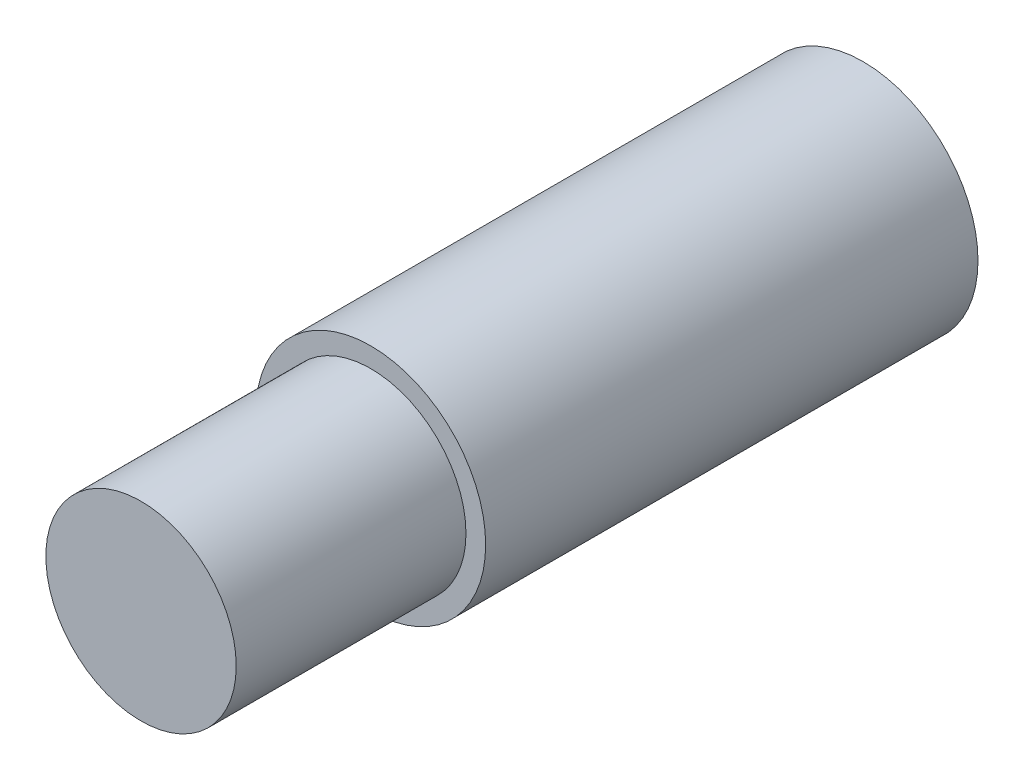
SolidWorks part; units mm, degrees
ref_plane "Front Plane" through (0, 0, 0) normal (0, 0, 1) x (1, 0, 0)
ref_plane "Top Plane" through (0, 0, 0) normal (0, 1, 0) x (1, 0, 0)
ref_plane "Right Plane" through (0, 0, 0) normal (1, 0, 0) x (0, 0, -1)
sketch "Sketch1" plane through (0, 0, 0) normal (0, 0, 1) x (1, 0, 0)
  circle A0 centre (0, 0) radius 3.5
  dimension "D1" = 7
extrude "Boss-Extrude1" add sketch "Sketch1" along normal blind 15
sketch "Sketch2" plane through (0, 0, 15) normal (0, 0, 1) x (1, 0, 0)
  circle A0 centre (0, 0) radius 2.9
  dimension "D1" = 5.8
extrude "Boss-Extrude2" add sketch "Sketch2" along normal blind 7
